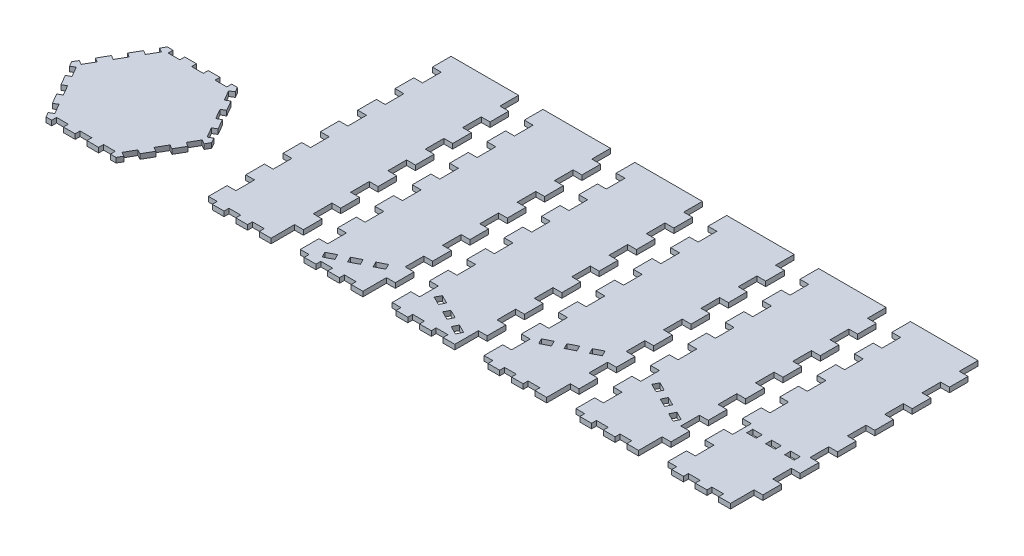
SolidWorks part; units mm, degrees
ref_plane "Front Plane" through (0, 0, 0) normal (0, 0, 1) x (1, 0, 0)
ref_plane "Top Plane" through (0, 0, 0) normal (0, 1, 0) x (1, 0, 0)
ref_plane "Right Plane" through (0, 0, 0) normal (1, 0, 0) x (0, 0, -1)
sketch "Sketch1" plane through (0, 0, 0) normal (0, 1, 0) x (1, 0, 0)
  line L0 (-22.87, -39.612) -> (-19.175, -39.612)
  line L13 (-19.175, -39.612) -> (-19.175, -36.412)
  line L14 (-19.175, -36.412) -> (-11.505, -36.412)
  line L15 (-11.505, -36.412) -> (-11.505, -39.612)
  line L16 (-11.505, -39.612) -> (-3.835, -39.612)
  line L17 (-3.835, -39.612) -> (-3.835, -36.412)
  line L18 (-3.835, -36.412) -> (3.835, -36.412)
  line L19 (3.835, -36.412) -> (3.835, -39.612)
  line L21 (-45.74, 0) -> (-43.8925, -3.2)
  line L22 (3.835, -39.612) -> (11.505, -39.612)
  line L23 (11.505, -39.612) -> (11.505, -36.412)
  line L24 (11.505, -36.412) -> (19.175, -36.412)
  line L25 (19.175, -36.412) -> (19.175, -39.612)
  line L26 (19.175, -39.612) -> (22.87, -39.612)
  line L27 (22.87, -39.612) -> (24.7175, -36.412)
  line L28 (45.74, 0) -> (22.87, 39.612) construction
  line L29 (24.7175, -36.412) -> (21.9462, -34.812)
  line L30 (21.9462, -34.812) -> (25.7812, -28.1696)
  line L31 (25.7812, -28.1696) -> (28.5525, -29.7696)
  line L32 (28.5525, -29.7696) -> (32.3875, -23.1272)
  line L33 (32.3875, -23.1272) -> (29.6162, -21.5272)
  line L34 (29.6162, -21.5272) -> (33.4512, -14.8848)
  line L35 (33.4512, -14.8848) -> (36.2225, -16.4848)
  line L36 (36.2225, -16.4848) -> (40.0575, -9.8424)
  line L37 (40.0575, -9.8424) -> (37.2862, -8.2424)
  line L38 (37.2862, -8.2424) -> (41.1212, -1.6)
  line L39 (41.1212, -1.6) -> (43.8925, -3.2)
  line L40 (43.8925, -3.2) -> (45.74, 0)
  line L41 (45.74, 0) -> (43.8925, 3.2)
  line L42 (22.87, 39.612) -> (-22.87, 39.612) construction
  line L43 (-22.87, 39.612) -> (-45.74, 0) construction
  line L44 (43.8925, 3.2) -> (41.1212, 1.6)
  line L45 (41.1212, 1.6) -> (37.2862, 8.2424)
  line L46 (37.2862, 8.2424) -> (40.0575, 9.8424)
  line L47 (40.0575, 9.8424) -> (36.2225, 16.4848)
  line L48 (36.2225, 16.4848) -> (33.4512, 14.8848)
  line L49 (33.4512, 14.8848) -> (29.6162, 21.5272)
  line L50 (29.6162, 21.5272) -> (32.3875, 23.1272)
  line L51 (32.3875, 23.1272) -> (28.5525, 29.7696)
  line L52 (28.5525, 29.7696) -> (25.7812, 28.1696)
  line L53 (25.7812, 28.1696) -> (21.9462, 34.812)
  line L54 (21.9462, 34.812) -> (24.7175, 36.412)
  line L55 (24.7175, 36.412) -> (22.87, 39.612)
  line L56 (22.87, 39.612) -> (19.175, 39.612)
  line L57 (-45.74, 0) -> (-22.87, -39.612) construction
  line L58 (-22.87, -39.612) -> (22.87, -39.612) construction
  line L59 (19.175, 39.612) -> (19.175, 36.412)
  line L60 (19.175, 36.412) -> (11.505, 36.412)
  line L61 (11.505, 36.412) -> (11.505, 39.612)
  line L62 (11.505, 39.612) -> (3.835, 39.612)
  line L63 (3.835, 39.612) -> (3.835, 36.412)
  line L64 (3.835, 36.412) -> (-3.835, 36.412)
  line L65 (-3.835, 36.412) -> (-3.835, 39.612)
  line L66 (-3.835, 39.612) -> (-11.505, 39.612)
  line L67 (-11.505, 39.612) -> (-11.505, 36.412)
  line L68 (-11.505, 36.412) -> (-19.175, 36.412)
  line L69 (-19.175, 36.412) -> (-19.175, 39.612)
  line L70 (-19.175, 39.612) -> (-22.87, 39.612)
  line L71 (-22.87, 39.612) -> (-24.7175, 36.412)
  line L72 (22.87, -39.612) -> (45.74, 0) construction
  line L73 (-43.8925, -3.2) -> (-41.1212, -1.6)
  line L74 (-24.7175, 36.412) -> (-21.9462, 34.812)
  line L75 (-21.9462, 34.812) -> (-25.7812, 28.1696)
  line L76 (-25.7812, 28.1696) -> (-28.5525, 29.7696)
  line L77 (-28.5525, 29.7696) -> (-32.3875, 23.1272)
  line L78 (-32.3875, 23.1272) -> (-29.6162, 21.5272)
  line L79 (-29.6162, 21.5272) -> (-33.4512, 14.8848)
  line L80 (-33.4512, 14.8848) -> (-36.2225, 16.4848)
  line L81 (-36.2225, 16.4848) -> (-40.0575, 9.8424)
  line L82 (-40.0575, 9.8424) -> (-37.2862, 8.2424)
  line L83 (-37.2862, 8.2424) -> (-41.1212, 1.6)
  line L84 (-41.1212, 1.6) -> (-43.8925, 3.2)
  line L85 (-43.8925, 3.2) -> (-45.74, 0)
  line L86 (-41.1212, -1.6) -> (-37.2862, -8.2424)
  line L87 (-37.2862, -8.2424) -> (-40.0575, -9.8424)
  line L88 (-40.0575, -9.8424) -> (-36.2225, -16.4848)
  line L89 (-36.2225, -16.4848) -> (-33.4512, -14.8848)
  line L90 (-33.4512, -14.8848) -> (-29.6162, -21.5272)
  line L91 (-29.6162, -21.5272) -> (-32.3875, -23.1272)
  line L92 (-32.3875, -23.1272) -> (-28.5525, -29.7696)
  line L93 (-28.5525, -29.7696) -> (-25.7812, -28.1696)
  line L94 (-25.7812, -28.1696) -> (-21.9462, -34.812)
  line L95 (-21.9462, -34.812) -> (-24.7175, -36.412)
  line L96 (-24.7175, -36.412) -> (-22.87, -39.612)
  line L97 (-21.9462, -34.812) -> (-19.175, -39.612) construction
  line L102 (19.175, -36.412) -> (24.7175, -36.412) construction
  line L103 (-19.175, -36.412) -> (-24.7175, -36.412) construction
  line L104 (80.8115, -34.6947) -> (88.4815, -34.6947)
  line L105 (88.4815, -34.6947) -> (88.4815, -31.4947)
  line L106 (88.4815, -31.4947) -> (96.1515, -31.4947)
  line L107 (96.1515, -31.4947) -> (96.1515, -34.6947)
  line L108 (96.1515, -34.6947) -> (103.8215, -34.6947)
  line L109 (103.8215, -34.6947) -> (103.8215, -31.4947)
  line L110 (103.8215, -31.4947) -> (111.4914, -31.4947)
  line L111 (111.4914, -31.4947) -> (111.4914, -34.6947)
  line L112 (111.4914, -34.6947) -> (119.1614, -34.6947)
  line L113 (80.8115, -34.6947) -> (80.8115, -31.4947)
  line L114 (80.8115, -31.4947) -> (75.0689, -31.4947)
  line L115 (75.0689, -31.4947) -> (75.0689, -19.3064)
  line L116 (75.0689, -19.3064) -> (80.8115, -19.3064)
  line L117 (80.8115, -19.3064) -> (80.8115, -7.1181)
  line L118 (80.8115, -7.1181) -> (75.0689, -7.1181)
  line L121 (119.1614, -7.1181) -> (124.904, -7.1181)
  line L122 (124.904, -7.1181) -> (124.904, -19.3064)
  line L123 (124.904, -19.3064) -> (119.1614, -19.3064)
  line L124 (119.1614, -19.3064) -> (119.1614, -34.6947)
  line L126 (21.9462, -34.812) -> (19.175, -39.612) construction
  line L250 (140.8115, -34.6947) -> (148.4815, -34.6947)
  line L265 (148.4815, -34.6947) -> (148.4815, -31.4947)
  line L266 (148.4815, -31.4947) -> (156.1515, -31.4947)
  line L267 (156.1515, -31.4947) -> (156.1515, -34.6947)
  line L268 (156.1515, -34.6947) -> (163.8215, -34.6947)
  line L269 (163.8215, -34.6947) -> (163.8215, -31.4947)
  line L270 (75.0689, -7.1181) -> (75.0689, 5.0702)
  line L271 (75.0689, 5.0702) -> (80.8115, 5.0702)
  line L272 (80.8115, 5.0702) -> (80.8115, 17.2585)
  line L273 (80.8115, 17.2585) -> (75.0689, 17.2585)
  line L274 (75.0689, 17.2585) -> (75.0689, 29.4468)
  line L275 (75.0689, 29.4468) -> (80.8115, 29.4468)
  line L276 (80.8115, 29.4468) -> (80.8115, 41.6351)
  line L277 (80.8115, 41.6351) -> (75.0689, 41.6351)
  line L278 (75.0689, 41.6351) -> (75.0689, 53.8234)
  line L279 (75.0689, 53.8234) -> (80.8115, 53.8234)
  line L280 (80.8115, 53.8234) -> (80.8115, 66.0118)
  line L281 (80.8115, 66.0118) -> (75.0689, 66.0118)
  line L282 (75.0689, 66.0118) -> (75.0689, 78.2001)
  line L283 (75.0689, 78.2001) -> (80.8115, 78.2001)
  line L284 (80.8115, 78.2001) -> (80.8115, 90.3884)
  line L285 (80.8115, 90.3884) -> (75.0689, 90.3884)
  line L286 (75.0689, 90.3884) -> (75.0689, 102.5767)
  line L287 (75.0689, 102.5767) -> (80.8115, 102.5767)
  line L288 (80.8115, 102.5767) -> (80.8115, 114.765)
  line L289 (80.8115, 114.765) -> (75.0689, 114.765)
  line L290 (75.0689, 114.765) -> (75.0689, 126.9533)
  line L291 (119.1614, -7.1181) -> (119.1614, 5.0702)
  line L292 (119.1614, 5.0702) -> (124.904, 5.0702)
  line L293 (124.904, 5.0702) -> (124.904, 17.2585)
  line L294 (124.904, 17.2585) -> (119.1614, 17.2585)
  line L295 (119.1614, 17.2585) -> (119.1614, 29.4468)
  line L296 (119.1614, 29.4468) -> (124.904, 29.4468)
  line L297 (124.904, 29.4468) -> (124.904, 41.6351)
  line L298 (124.904, 41.6351) -> (119.1614, 41.6351)
  line L299 (119.1614, 41.6351) -> (119.1614, 53.8234)
  line L300 (119.1614, 53.8234) -> (124.904, 53.8234)
  line L301 (124.904, 53.8234) -> (124.904, 66.0118)
  line L302 (124.904, 66.0118) -> (119.1614, 66.0118)
  line L303 (119.1614, 66.0118) -> (119.1614, 78.2001)
  line L304 (119.1614, 78.2001) -> (124.904, 78.2001)
  line L305 (124.904, 78.2001) -> (124.904, 90.3884)
  line L306 (124.904, 90.3884) -> (119.1614, 90.3884)
  line L307 (119.1614, 90.3884) -> (119.1614, 102.5767)
  line L308 (119.1614, 102.5767) -> (124.904, 102.5767)
  line L309 (124.904, 102.5767) -> (124.904, 114.765)
  line L310 (124.904, 114.765) -> (119.1614, 114.765)
  line L311 (119.1614, 114.765) -> (119.1614, 126.9533)
  line L312 (163.8215, -31.4947) -> (171.4914, -31.4947)
  line L313 (171.4914, -31.4947) -> (171.4914, -34.6947)
  line L314 (171.4914, -34.6947) -> (179.1614, -34.6947)
  line L315 (140.8115, -34.6947) -> (140.8115, -31.4947)
  line L316 (140.8115, -31.4947) -> (135.0689, -31.4947)
  line L317 (135.0689, -31.4947) -> (135.0689, -19.3064)
  line L318 (135.0689, -19.3064) -> (140.8115, -19.3064)
  line L319 (140.8115, -19.3064) -> (140.8115, -7.1181)
  line L320 (140.8115, -7.1181) -> (135.0689, -7.1181)
  line L322 (179.1614, -7.1181) -> (184.904, -7.1181)
  line L323 (184.904, -7.1181) -> (184.904, -19.3064)
  line L324 (184.904, -19.3064) -> (179.1614, -19.3064)
  line L325 (179.1614, -19.3064) -> (179.1614, -34.6947)
  line L326 (135.0689, -7.1181) -> (135.0689, 5.0702)
  line L327 (135.0689, 5.0702) -> (140.8115, 5.0702)
  line L328 (140.8115, 5.0702) -> (140.8115, 17.2585)
  line L329 (140.8115, 17.2585) -> (135.0689, 17.2585)
  line L330 (135.0689, 17.2585) -> (135.0689, 29.4468)
  line L331 (135.0689, 29.4468) -> (140.8115, 29.4468)
  line L332 (140.8115, 29.4468) -> (140.8115, 41.6351)
  line L333 (140.8115, 41.6351) -> (135.0689, 41.6351)
  line L334 (135.0689, 41.6351) -> (135.0689, 53.8234)
  line L335 (135.0689, 53.8234) -> (140.8115, 53.8234)
  line L336 (140.8115, 53.8234) -> (140.8115, 66.0118)
  line L337 (140.8115, 66.0118) -> (135.0689, 66.0118)
  line L338 (135.0689, 66.0118) -> (135.0689, 78.2001)
  line L339 (135.0689, 78.2001) -> (140.8115, 78.2001)
  line L340 (140.8115, 78.2001) -> (140.8115, 90.3884)
  line L341 (140.8115, 90.3884) -> (135.0689, 90.3884)
  line L342 (135.0689, 90.3884) -> (135.0689, 102.5767)
  line L343 (135.0689, 102.5767) -> (140.8115, 102.5767)
  line L344 (140.8115, 102.5767) -> (140.8115, 114.765)
  line L345 (140.8115, 114.765) -> (135.0689, 114.765)
  line L346 (135.0689, 114.765) -> (135.0689, 126.9533)
  line L347 (179.1614, -7.1181) -> (179.1614, 5.0702)
  line L348 (179.1614, 5.0702) -> (184.904, 5.0702)
  line L349 (184.904, 5.0702) -> (184.904, 17.2585)
  line L350 (184.904, 17.2585) -> (179.1614, 17.2585)
  line L351 (179.1614, 17.2585) -> (179.1614, 29.4468)
  line L352 (179.1614, 29.4468) -> (184.904, 29.4468)
  line L353 (184.904, 29.4468) -> (184.904, 41.6351)
  line L354 (184.904, 41.6351) -> (179.1614, 41.6351)
  line L355 (179.1614, 41.6351) -> (179.1614, 53.8234)
  line L356 (179.1614, 53.8234) -> (184.904, 53.8234)
  line L357 (184.904, 53.8234) -> (184.904, 66.0118)
  line L358 (184.904, 66.0118) -> (179.1614, 66.0118)
  line L359 (179.1614, 66.0118) -> (179.1614, 78.2001)
  line L360 (179.1614, 78.2001) -> (184.904, 78.2001)
  line L361 (184.904, 78.2001) -> (184.904, 90.3884)
  line L362 (184.904, 90.3884) -> (179.1614, 90.3884)
  line L363 (179.1614, 90.3884) -> (179.1614, 102.5767)
  line L364 (179.1614, 102.5767) -> (184.904, 102.5767)
  line L365 (184.904, 102.5767) -> (184.904, 114.765)
  line L366 (184.904, 114.765) -> (179.1614, 114.765)
  line L367 (179.1614, 114.765) -> (179.1614, 126.9533)
  line L369 (200.8115, -34.6947) -> (208.4815, -34.6947)
  line L370 (208.4815, -34.6947) -> (208.4815, -31.4947)
  line L371 (208.4815, -31.4947) -> (216.1515, -31.4947)
  line L372 (216.1515, -31.4947) -> (216.1515, -34.6947)
  line L373 (216.1515, -34.6947) -> (223.8215, -34.6947)
  line L374 (223.8215, -34.6947) -> (223.8215, -31.4947)
  line L375 (223.8215, -31.4947) -> (231.4914, -31.4947)
  line L376 (231.4914, -31.4947) -> (231.4914, -34.6947)
  line L377 (231.4914, -34.6947) -> (239.1614, -34.6947)
  line L378 (200.8115, -34.6947) -> (200.8115, -31.4947)
  line L379 (200.8115, -31.4947) -> (195.0689, -31.4947)
  line L380 (195.0689, -31.4947) -> (195.0689, -19.3064)
  line L381 (195.0689, -19.3064) -> (200.8115, -19.3064)
  line L382 (200.8115, -19.3064) -> (200.8115, -7.1181)
  line L383 (200.8115, -7.1181) -> (195.0689, -7.1181)
  line L385 (239.1614, -7.1181) -> (244.904, -7.1181)
  line L386 (244.904, -7.1181) -> (244.904, -19.3064)
  line L387 (244.904, -19.3064) -> (239.1614, -19.3064)
  line L388 (239.1614, -19.3064) -> (239.1614, -34.6947)
  line L389 (195.0689, -7.1181) -> (195.0689, 5.0702)
  line L390 (195.0689, 5.0702) -> (200.8115, 5.0702)
  line L391 (200.8115, 5.0702) -> (200.8115, 17.2585)
  line L392 (200.8115, 17.2585) -> (195.0689, 17.2585)
  line L393 (195.0689, 17.2585) -> (195.0689, 29.4468)
  line L394 (195.0689, 29.4468) -> (200.8115, 29.4468)
  line L395 (200.8115, 29.4468) -> (200.8115, 41.6351)
  line L396 (200.8115, 41.6351) -> (195.0689, 41.6351)
  line L397 (195.0689, 41.6351) -> (195.0689, 53.8234)
  line L398 (195.0689, 53.8234) -> (200.8115, 53.8234)
  line L399 (200.8115, 53.8234) -> (200.8115, 66.0118)
  line L400 (200.8115, 66.0118) -> (195.0689, 66.0118)
  line L401 (195.0689, 66.0118) -> (195.0689, 78.2001)
  line L402 (195.0689, 78.2001) -> (200.8115, 78.2001)
  line L403 (200.8115, 78.2001) -> (200.8115, 90.3884)
  line L404 (200.8115, 90.3884) -> (195.0689, 90.3884)
  line L405 (195.0689, 90.3884) -> (195.0689, 102.5767)
  line L406 (195.0689, 102.5767) -> (200.8115, 102.5767)
  line L407 (200.8115, 102.5767) -> (200.8115, 114.765)
  line L408 (200.8115, 114.765) -> (195.0689, 114.765)
  line L409 (195.0689, 114.765) -> (195.0689, 126.9533)
  line L410 (239.1614, -7.1181) -> (239.1614, 5.0702)
  line L411 (239.1614, 5.0702) -> (244.904, 5.0702)
  line L412 (244.904, 5.0702) -> (244.904, 17.2585)
  line L413 (244.904, 17.2585) -> (239.1614, 17.2585)
  line L414 (239.1614, 17.2585) -> (239.1614, 29.4468)
  line L415 (239.1614, 29.4468) -> (244.904, 29.4468)
  line L416 (244.904, 29.4468) -> (244.904, 41.6351)
  line L417 (244.904, 41.6351) -> (239.1614, 41.6351)
  line L418 (239.1614, 41.6351) -> (239.1614, 53.8234)
  line L419 (239.1614, 53.8234) -> (244.904, 53.8234)
  line L420 (244.904, 53.8234) -> (244.904, 66.0118)
  line L421 (244.904, 66.0118) -> (239.1614, 66.0118)
  line L422 (239.1614, 66.0118) -> (239.1614, 78.2001)
  line L423 (239.1614, 78.2001) -> (244.904, 78.2001)
  line L424 (244.904, 78.2001) -> (244.904, 90.3884)
  line L425 (244.904, 90.3884) -> (239.1614, 90.3884)
  line L426 (239.1614, 90.3884) -> (239.1614, 102.5767)
  line L427 (239.1614, 102.5767) -> (244.904, 102.5767)
  line L428 (244.904, 102.5767) -> (244.904, 114.765)
  line L429 (244.904, 114.765) -> (239.1614, 114.765)
  line L430 (239.1614, 114.765) -> (239.1614, 126.9533)
  line L432 (260.8115, -34.6947) -> (268.4815, -34.6947)
  line L433 (268.4815, -34.6947) -> (268.4815, -31.4947)
  line L434 (268.4815, -31.4947) -> (276.1515, -31.4947)
  line L435 (276.1515, -31.4947) -> (276.1515, -34.6947)
  line L436 (276.1515, -34.6947) -> (283.8215, -34.6947)
  line L437 (283.8215, -34.6947) -> (283.8215, -31.4947)
  line L438 (283.8215, -31.4947) -> (291.4914, -31.4947)
  line L439 (291.4914, -31.4947) -> (291.4914, -34.6947)
  line L440 (291.4914, -34.6947) -> (299.1614, -34.6947)
  line L441 (260.8115, -34.6947) -> (260.8115, -31.4947)
  line L442 (260.8115, -31.4947) -> (255.0689, -31.4947)
  line L443 (255.0689, -31.4947) -> (255.0689, -19.3064)
  line L444 (255.0689, -19.3064) -> (260.8115, -19.3064)
  line L445 (260.8115, -19.3064) -> (260.8115, -7.1181)
  line L446 (260.8115, -7.1181) -> (255.0689, -7.1181)
  line L448 (299.1614, -7.1181) -> (304.904, -7.1181)
  line L449 (304.904, -7.1181) -> (304.904, -19.3064)
  line L450 (304.904, -19.3064) -> (299.1614, -19.3064)
  line L451 (299.1614, -19.3064) -> (299.1614, -34.6947)
  line L452 (255.0689, -7.1181) -> (255.0689, 5.0702)
  line L453 (255.0689, 5.0702) -> (260.8115, 5.0702)
  line L454 (260.8115, 5.0702) -> (260.8115, 17.2585)
  line L455 (260.8115, 17.2585) -> (255.0689, 17.2585)
  line L456 (255.0689, 17.2585) -> (255.0689, 29.4468)
  line L457 (255.0689, 29.4468) -> (260.8115, 29.4468)
  line L458 (260.8115, 29.4468) -> (260.8115, 41.6351)
  line L459 (260.8115, 41.6351) -> (255.0689, 41.6351)
  line L460 (255.0689, 41.6351) -> (255.0689, 53.8234)
  line L461 (255.0689, 53.8234) -> (260.8115, 53.8234)
  line L462 (260.8115, 53.8234) -> (260.8115, 66.0118)
  line L463 (260.8115, 66.0118) -> (255.0689, 66.0118)
  line L464 (255.0689, 66.0118) -> (255.0689, 78.2001)
  line L465 (255.0689, 78.2001) -> (260.8115, 78.2001)
  line L466 (260.8115, 78.2001) -> (260.8115, 90.3884)
  line L467 (260.8115, 90.3884) -> (255.0689, 90.3884)
  line L468 (255.0689, 90.3884) -> (255.0689, 102.5767)
  line L469 (255.0689, 102.5767) -> (260.8115, 102.5767)
  line L470 (260.8115, 102.5767) -> (260.8115, 114.765)
  line L471 (260.8115, 114.765) -> (255.0689, 114.765)
  line L472 (255.0689, 114.765) -> (255.0689, 126.9533)
  line L473 (299.1614, -7.1181) -> (299.1614, 5.0702)
  line L474 (299.1614, 5.0702) -> (304.904, 5.0702)
  line L475 (304.904, 5.0702) -> (304.904, 17.2585)
  line L476 (304.904, 17.2585) -> (299.1614, 17.2585)
  line L477 (299.1614, 17.2585) -> (299.1614, 29.4468)
  line L478 (299.1614, 29.4468) -> (304.904, 29.4468)
  line L479 (304.904, 29.4468) -> (304.904, 41.6351)
  line L480 (304.904, 41.6351) -> (299.1614, 41.6351)
  line L481 (299.1614, 41.6351) -> (299.1614, 53.8234)
  line L482 (299.1614, 53.8234) -> (304.904, 53.8234)
  line L483 (304.904, 53.8234) -> (304.904, 66.0118)
  line L484 (304.904, 66.0118) -> (299.1614, 66.0118)
  line L485 (299.1614, 66.0118) -> (299.1614, 78.2001)
  line L486 (299.1614, 78.2001) -> (304.904, 78.2001)
  line L487 (304.904, 78.2001) -> (304.904, 90.3884)
  line L488 (304.904, 90.3884) -> (299.1614, 90.3884)
  line L489 (299.1614, 90.3884) -> (299.1614, 102.5767)
  line L490 (299.1614, 102.5767) -> (304.904, 102.5767)
  line L491 (304.904, 102.5767) -> (304.904, 114.765)
  line L492 (304.904, 114.765) -> (299.1614, 114.765)
  line L493 (299.1614, 114.765) -> (299.1614, 126.9533)
  line L495 (320.8115, -34.6947) -> (328.4815, -34.6947)
  line L496 (328.4815, -34.6947) -> (328.4815, -31.4947)
  line L497 (328.4815, -31.4947) -> (336.1515, -31.4947)
  line L498 (336.1515, -31.4947) -> (336.1515, -34.6947)
  line L499 (336.1515, -34.6947) -> (343.8215, -34.6947)
  line L500 (343.8215, -34.6947) -> (343.8215, -31.4947)
  line L501 (343.8215, -31.4947) -> (351.4914, -31.4947)
  line L502 (351.4914, -31.4947) -> (351.4914, -34.6947)
  line L503 (351.4914, -34.6947) -> (359.1614, -34.6947)
  line L504 (320.8115, -34.6947) -> (320.8115, -31.4947)
  line L505 (320.8115, -31.4947) -> (315.0689, -31.4947)
  line L506 (315.0689, -31.4947) -> (315.0689, -19.3064)
  line L507 (315.0689, -19.3064) -> (320.8115, -19.3064)
  line L508 (320.8115, -19.3064) -> (320.8115, -7.1181)
  line L509 (320.8115, -7.1181) -> (315.0689, -7.1181)
  line L511 (359.1614, -7.1181) -> (364.904, -7.1181)
  line L512 (364.904, -7.1181) -> (364.904, -19.3064)
  line L513 (364.904, -19.3064) -> (359.1614, -19.3064)
  line L514 (359.1614, -19.3064) -> (359.1614, -34.6947)
  line L515 (315.0689, -7.1181) -> (315.0689, 5.0702)
  line L516 (315.0689, 5.0702) -> (320.8115, 5.0702)
  line L517 (320.8115, 5.0702) -> (320.8115, 17.2585)
  line L518 (320.8115, 17.2585) -> (315.0689, 17.2585)
  line L519 (315.0689, 17.2585) -> (315.0689, 29.4468)
  line L520 (315.0689, 29.4468) -> (320.8115, 29.4468)
  line L521 (320.8115, 29.4468) -> (320.8115, 41.6351)
  line L522 (320.8115, 41.6351) -> (315.0689, 41.6351)
  line L523 (315.0689, 41.6351) -> (315.0689, 53.8234)
  line L524 (315.0689, 53.8234) -> (320.8115, 53.8234)
  line L525 (320.8115, 53.8234) -> (320.8115, 66.0118)
  line L526 (320.8115, 66.0118) -> (315.0689, 66.0118)
  line L527 (315.0689, 66.0118) -> (315.0689, 78.2001)
  line L528 (315.0689, 78.2001) -> (320.8115, 78.2001)
  line L529 (320.8115, 78.2001) -> (320.8115, 90.3884)
  line L530 (320.8115, 90.3884) -> (315.0689, 90.3884)
  line L531 (315.0689, 90.3884) -> (315.0689, 102.5767)
  line L532 (315.0689, 102.5767) -> (320.8115, 102.5767)
  line L533 (320.8115, 102.5767) -> (320.8115, 114.765)
  line L534 (320.8115, 114.765) -> (315.0689, 114.765)
  line L535 (315.0689, 114.765) -> (315.0689, 126.9533)
  line L536 (359.1614, -7.1181) -> (359.1614, 5.0702)
  line L537 (359.1614, 5.0702) -> (364.904, 5.0702)
  line L538 (364.904, 5.0702) -> (364.904, 17.2585)
  line L539 (364.904, 17.2585) -> (359.1614, 17.2585)
  line L540 (359.1614, 17.2585) -> (359.1614, 29.4468)
  line L541 (359.1614, 29.4468) -> (364.904, 29.4468)
  line L542 (364.904, 29.4468) -> (364.904, 41.6351)
  line L543 (364.904, 41.6351) -> (359.1614, 41.6351)
  line L544 (359.1614, 41.6351) -> (359.1614, 53.8234)
  line L545 (359.1614, 53.8234) -> (364.904, 53.8234)
  line L546 (364.904, 53.8234) -> (364.904, 66.0118)
  line L547 (364.904, 66.0118) -> (359.1614, 66.0118)
  line L548 (359.1614, 66.0118) -> (359.1614, 78.2001)
  line L549 (359.1614, 78.2001) -> (364.904, 78.2001)
  line L550 (364.904, 78.2001) -> (364.904, 90.3884)
  line L551 (364.904, 90.3884) -> (359.1614, 90.3884)
  line L552 (359.1614, 90.3884) -> (359.1614, 102.5767)
  line L553 (359.1614, 102.5767) -> (364.904, 102.5767)
  line L554 (364.904, 102.5767) -> (364.904, 114.765)
  line L555 (364.904, 114.765) -> (359.1614, 114.765)
  line L556 (359.1614, 114.765) -> (359.1614, 126.9533)
  line L558 (380.8115, -34.6947) -> (388.4815, -34.6947)
  line L559 (388.4815, -34.6947) -> (388.4815, -31.4947)
  line L560 (388.4815, -31.4947) -> (396.1515, -31.4947)
  line L561 (396.1515, -31.4947) -> (396.1515, -34.6947)
  line L562 (396.1515, -34.6947) -> (403.8215, -34.6947)
  line L563 (403.8215, -34.6947) -> (403.8215, -31.4947)
  line L564 (403.8215, -31.4947) -> (411.4914, -31.4947)
  line L565 (411.4914, -31.4947) -> (411.4914, -34.6947)
  line L566 (411.4914, -34.6947) -> (419.1614, -34.6947)
  line L567 (380.8115, -34.6947) -> (380.8115, -31.4947)
  line L568 (380.8115, -31.4947) -> (375.0689, -31.4947)
  line L569 (375.0689, -31.4947) -> (375.0689, -19.3064)
  line L570 (375.0689, -19.3064) -> (380.8115, -19.3064)
  line L571 (380.8115, -19.3064) -> (380.8115, -7.1181)
  line L572 (380.8115, -7.1181) -> (375.0689, -7.1181)
  line L574 (419.1614, -7.1181) -> (424.904, -7.1181)
  line L575 (424.904, -7.1181) -> (424.904, -19.3064)
  line L576 (424.904, -19.3064) -> (419.1614, -19.3064)
  line L577 (419.1614, -19.3064) -> (419.1614, -34.6947)
  line L578 (375.0689, -7.1181) -> (375.0689, 5.0702)
  line L579 (375.0689, 5.0702) -> (380.8115, 5.0702)
  line L580 (380.8115, 5.0702) -> (380.8115, 17.2585)
  line L581 (380.8115, 17.2585) -> (375.0689, 17.2585)
  line L582 (375.0689, 17.2585) -> (375.0689, 29.4468)
  line L583 (375.0689, 29.4468) -> (380.8115, 29.4468)
  line L584 (380.8115, 29.4468) -> (380.8115, 41.6351)
  line L585 (380.8115, 41.6351) -> (375.0689, 41.6351)
  line L586 (375.0689, 41.6351) -> (375.0689, 53.8234)
  line L587 (375.0689, 53.8234) -> (380.8115, 53.8234)
  line L588 (380.8115, 53.8234) -> (380.8115, 66.0118)
  line L589 (380.8115, 66.0118) -> (375.0689, 66.0118)
  line L590 (375.0689, 66.0118) -> (375.0689, 78.2001)
  line L591 (375.0689, 78.2001) -> (380.8115, 78.2001)
  line L592 (380.8115, 78.2001) -> (380.8115, 90.3884)
  line L593 (380.8115, 90.3884) -> (375.0689, 90.3884)
  line L594 (375.0689, 90.3884) -> (375.0689, 102.5767)
  line L595 (375.0689, 102.5767) -> (380.8115, 102.5767)
  line L596 (380.8115, 102.5767) -> (380.8115, 114.765)
  line L597 (380.8115, 114.765) -> (375.0689, 114.765)
  line L598 (375.0689, 114.765) -> (375.0689, 126.9533)
  line L599 (419.1614, -7.1181) -> (419.1614, 5.0702)
  line L600 (419.1614, 5.0702) -> (424.904, 5.0702)
  line L601 (424.904, 5.0702) -> (424.904, 17.2585)
  line L602 (424.904, 17.2585) -> (419.1614, 17.2585)
  line L603 (419.1614, 17.2585) -> (419.1614, 29.4468)
  line L604 (419.1614, 29.4468) -> (424.904, 29.4468)
  line L605 (424.904, 29.4468) -> (424.904, 41.6351)
  line L606 (424.904, 41.6351) -> (419.1614, 41.6351)
  line L607 (419.1614, 41.6351) -> (419.1614, 53.8234)
  line L608 (419.1614, 53.8234) -> (424.904, 53.8234)
  line L609 (424.904, 53.8234) -> (424.904, 66.0118)
  line L610 (424.904, 66.0118) -> (419.1614, 66.0118)
  line L611 (419.1614, 66.0118) -> (419.1614, 78.2001)
  line L612 (419.1614, 78.2001) -> (424.904, 78.2001)
  line L613 (424.904, 78.2001) -> (424.904, 90.3884)
  line L614 (424.904, 90.3884) -> (419.1614, 90.3884)
  line L615 (419.1614, 90.3884) -> (419.1614, 102.5767)
  line L616 (419.1614, 102.5767) -> (424.904, 102.5767)
  line L617 (424.904, 102.5767) -> (424.904, 114.765)
  line L618 (424.904, 114.765) -> (419.1614, 114.765)
  line L619 (419.1614, 114.765) -> (419.1614, 126.9533)
  line L621 (144.6914, -25.0554) -> (150.2371, -22.2831)
  line L622 (144.6914, -25.0554) -> (146.4799, -28.6332)
  line L623 (146.4799, -28.6332) -> (152.0256, -25.861)
  line L624 (150.2371, -22.2831) -> (152.0256, -25.861)
  line L625 (155.7828, -19.5109) -> (161.3285, -16.7387)
  line L626 (155.7828, -19.5109) -> (157.5713, -23.0888)
  line L627 (157.5713, -23.0888) -> (163.117, -20.3166)
  line L628 (161.3285, -16.7387) -> (163.117, -20.3166)
  line L632 (166.8742, -13.9665) -> (172.4199, -11.1943)
  line L633 (166.8742, -13.9665) -> (168.6627, -17.5444)
  line L634 (168.6627, -17.5444) -> (174.2084, -14.7721)
  line L635 (172.4199, -11.1943) -> (174.2084, -14.7721)
  line L636 (119.1614, 126.9533) -> (75.0689, 126.9533)
  line L637 (135.0689, 126.9533) -> (179.1614, 126.9533)
  line L638 (195.0689, 126.9533) -> (239.1614, 126.9533)
  line L639 (255.0689, 126.9533) -> (299.1614, 126.9533)
  line L640 (315.0689, 126.9533) -> (359.1614, 126.9533)
  line L641 (375.0689, 126.9533) -> (419.1614, 126.9533)
  line L642 (-41.1212, -1.6) -> (-42.045, 0) construction
  line L643 (-42.045, 0) -> (-41.1212, 1.6) construction
  line L644 (41.1212, -1.6) -> (42.045, 0) construction
  line L645 (42.045, 0) -> (41.1212, 1.6) construction
  line L646 (-21.0225, -36.412) -> (-22.87, -39.612) construction
  line L647 (21.0225, -36.412) -> (22.87, -39.612) construction
  line L648 (138.9665, -31.4947) -> (146.1222, -27.9176) construction
  line L649 (173.8507, -14.0566) -> (181.0065, -10.4795) construction
  line L650 (189.9865, 136.633) -> (189.9865, -43.0289) construction
  line L651 (138.9665, -34.6947) -> (181.0065, -34.6947) construction
  line L652 (207.553, -11.1943) -> (205.7645, -14.7721)
  line L653 (211.3102, -17.5444) -> (205.7645, -14.7721)
  line L654 (213.0987, -13.9665) -> (211.3102, -17.5444)
  line L655 (213.0987, -13.9665) -> (207.553, -11.1943)
  line L656 (218.6444, -16.7387) -> (216.8559, -20.3166)
  line L657 (222.4016, -23.0888) -> (216.8559, -20.3166)
  line L658 (224.1901, -19.5109) -> (222.4016, -23.0888)
  line L659 (224.1901, -19.5109) -> (218.6444, -16.7387)
  line L660 (229.7358, -22.2831) -> (227.9473, -25.861)
  line L661 (233.493, -28.6332) -> (227.9473, -25.861)
  line L662 (235.2815, -25.0554) -> (233.493, -28.6332)
  line L663 (235.2815, -25.0554) -> (229.7358, -22.2831)
  line L664 (252.6938, -10.4795) -> (309.9865, -10.4795) construction
  line L665 (258.9665, -34.6947) -> (301.0065, -34.6947) construction
  line L666 (258.9665, -10.4795) -> (266.1222, -6.9025) construction
  line L667 (266.1222, -6.9025) -> (264.3337, -3.3246)
  line L668 (264.3337, -3.3246) -> (269.8794, -0.5524)
  line L669 (269.8794, -0.5524) -> (271.6679, -4.1302)
  line L670 (271.6679, -4.1302) -> (266.1222, -6.9025)
  line L671 (275.4251, 2.2199) -> (277.2136, -1.358)
  line L672 (277.2136, -1.358) -> (282.7593, 1.4142)
  line L673 (282.7593, 1.4142) -> (280.9708, 4.9921)
  line L674 (280.9708, 4.9921) -> (275.4251, 2.2199)
  line L675 (286.5165, 7.7643) -> (288.305, 4.1864)
  line L676 (288.305, 4.1864) -> (293.8507, 6.9586)
  line L677 (293.8507, 6.9586) -> (292.0622, 10.5365)
  line L678 (292.0622, 10.5365) -> (286.5165, 7.7643)
  line L679 (293.8507, 6.9586) -> (301.0065, 10.5357) construction
  line L680 (309.9865, 136.633) -> (309.9865, -43.0289) construction
  line L681 (327.9107, 10.5365) -> (333.4564, 7.7643)
  line L682 (326.1222, 6.9586) -> (327.9107, 10.5365)
  line L683 (331.6679, 4.1864) -> (326.1222, 6.9586)
  line L684 (333.4564, 7.7643) -> (331.6679, 4.1864)
  line L685 (339.0021, 4.9921) -> (344.5478, 2.2199)
  line L686 (337.2136, 1.4142) -> (339.0021, 4.9921)
  line L687 (342.7593, -1.358) -> (337.2136, 1.4142)
  line L688 (344.5478, 2.2199) -> (342.7593, -1.358)
  line L689 (348.305, -4.1302) -> (353.8507, -6.9025)
  line L690 (350.0935, -0.5524) -> (348.305, -4.1302)
  line L691 (355.6393, -3.3246) -> (350.0935, -0.5524)
  line L692 (353.8507, -6.9025) -> (355.6393, -3.3246)
  line L693 (384.4865, 14.5453) -> (384.4865, 10.5453)
  line L694 (384.4865, 10.5453) -> (390.6865, 10.5453)
  line L695 (390.6865, 10.5453) -> (390.6865, 14.5453)
  line L696 (390.6865, 14.5453) -> (384.4865, 14.5453)
  line L697 (396.8865, 14.5453) -> (396.8865, 10.5453)
  line L698 (396.8865, 10.5453) -> (403.0865, 10.5453)
  line L699 (403.0865, 10.5453) -> (403.0865, 14.5453)
  line L700 (403.0865, 14.5453) -> (396.8865, 14.5453)
  line L701 (409.2865, 14.5453) -> (409.2865, 10.5453)
  line L702 (409.2865, 10.5453) -> (415.4865, 10.5453)
  line L703 (415.4865, 10.5453) -> (415.4865, 14.5453)
  line L704 (415.4865, 14.5453) -> (409.2865, 14.5453)
  line L705 (384.4865, 10.5453) -> (380.8115, 10.5453) construction
  line L706 (415.4865, 10.5453) -> (419.1614, 10.5453) construction
  circle A0 centre (0, 0) radius 39.612 construction
  point P498 (304.904, -13.2122)
  point P544 (0, 0)
  point P545 (0, 0)
  point P546 (0, 0)
  dimension "D9" = 79.224
  dimension "D66" = 38.3499
  dimension "D79" = 3.2
  dimension "D10" = 38.3499
  dimension "D83" = 5.7426
  dimension "D45" = 5.7426
  dimension "D12" = 120
  dimension "D2" = 3.695
  dimension "D3" = 7.67
  dimension "D5" = 38.3499
  dimension "D11" = 12.1883
  dimension "D13" = 3.2
  dimension "D14" = 5.5426
  dimension "D86" = 15.3883
  dimension "D17" = 6.2
  dimension "D18" = 6.2
  dimension "D22" = 158.448
  dimension "D23" = 72.824
  dimension "D24" = 84.0899
  dimension "D25" = 42.045
  dimension "D19" = 6.2
  dimension "D20" = 10.165
  dimension "D26" = 5.0825
  dimension "D21" = 42.04
  dimension "D27" = 38.3499
  dimension "D28" = 1.845
  dimension "D32" = 21.0152
  dimension "D33" = 42.04
  dimension "D34" = 1.845
  dimension "D35" = 38.3499
  dimension "D36" = 4
  dimension "D37" = 6.2
  dimension "D38" = 6.2
  dimension "D39" = 6.2
  dimension "D40" = 8
  dimension "D41" = 26.56
  dimension "D42" = 10.165
  dimension "D43" = 5.0825
  dimension "D44" = 42.04
  dimension "D46" = 6.2
  dimension "D47" = 6.2
  dimension "D48" = 6.2
  dimension "D29" = 8
  dimension "D30" = 21.0152
  dimension "D16" = 3.2
  dimension "D31" = 4
  dimension "D49" = 4
  dimension "D15" = 6
extrude "Boss-Extrude3" add sketch "Sketch1" along normal blind 3.2
equation "\"Thick\"=3.2"
equation "\"angletabwidth\"=4"
equation "\"D26@Sketch1\"=\"D20@Sketch1\"/2"
equation "\"D28@Sketch1\"=(\"D21@Sketch1\"-\"D27@Sketch1\")/2"
equation "\"D34@Sketch1\"=(\"D33@Sketch1\"-\"D35@Sketch1\")/2"
equation "\"D43@Sketch1\"=\"D42@Sketch1\"/2"
